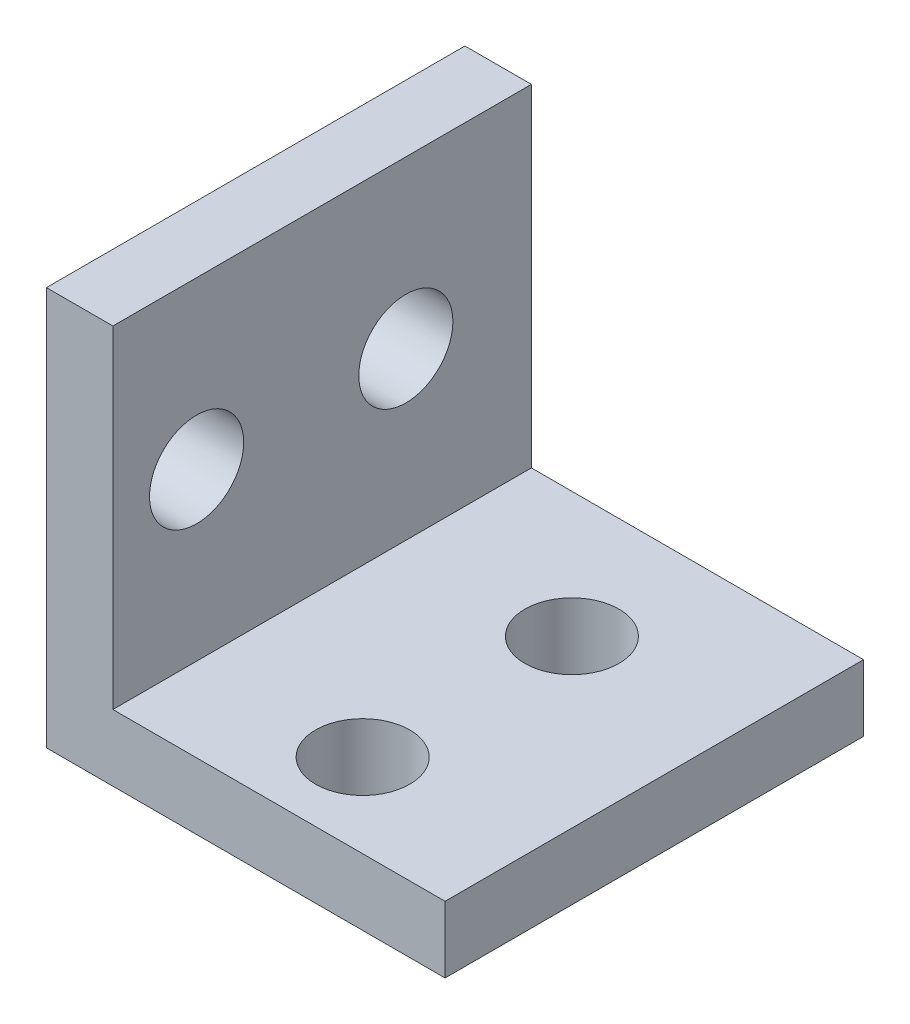
SolidWorks part; units mm, degrees
material "Aleación 6061"
ref_plane "Alzado" through (0, 0, 0) normal (0, 0, 1) x (1, 0, 0)
ref_plane "Planta" through (0, 0, 0) normal (0, 1, 0) x (1, 0, 0)
ref_plane "Vista lateral" through (0, 0, 0) normal (1, 0, 0) x (0, 0, -1)
sketch "Sk_Ala_1" plane through (0, 0, 0) normal (0, 0, 1) x (1, 0, 0)
  line L1 (0, 0) -> (19.05, 0)
  line L2 (0, 0) -> (0, 3.175)
  line L3 (0, 3.175) -> (19.05, 3.175)
  line L4 (19.05, 0) -> (19.05, 3.175)
  line L5 (0, 0) -> (19.05, 3.175) construction
  line L6 (0, 3.175) -> (19.05, 0) construction
  point P0 (9.525, 1.5875)
  dimension "D1" = 19.05
  dimension "D2" = 3.175
  dimension "D3" = 9.525
  dimension "D4" = 1.5875
extrude "Ala_1" add sketch "Sk_Ala_1" along normal blind 20
sketch "Sk_Ala_2" plane through (0, 0, 0) normal (0, 0, 1) x (1, 0, 0)
  line L1 (0, 0) -> (3.175, 0)
  line L2 (0, 0) -> (0, 19.05)
  line L3 (0, 19.05) -> (3.175, 19.05)
  line L4 (3.175, 0) -> (3.175, 19.05)
  line L5 (0, 0) -> (3.175, 19.05) construction
  line L6 (0, 19.05) -> (3.175, 0) construction
  point P0 (1.5875, 9.525)
  dimension "D1" = 3.175
  dimension "D2" = 19.05
  dimension "D3" = 1.5875
  dimension "D4" = 9.525
extrude "Ala_2" add sketch "Sk_Ala_2" along normal blind 20
sketch "Sk_Barrenos_ala_1" plane through (0, 0, 0) normal (0, 1, 0) x (1, 0, 0)
  circle A0 centre (11.1125, -6) radius 2.25
  circle A1 centre (11.1125, -16) radius 2.25
  dimension "D1" = 4.5
  dimension "D4" = 4.5
  dimension "D2" = 11.1125
  dimension "D3" = 6
  dimension "D5" = 11.1125
  dimension "D6" = 16
extrude "Barrenos_ala_1" cut sketch "Sk_Barrenos_ala_1" along normal blind 3.175
sketch "Sk_Barrenos_ala_2" plane through (0, 0, 0) normal (1, 0, 0) x (0, 0, -1)
  circle A0 centre (-6, 11.1125) radius 2.25
  circle A1 centre (-16, 11.1125) radius 2.25
  dimension "D1" = 4.5
  dimension "D4" = 4.5
  dimension "D2" = 6
  dimension "D3" = 11.1125
  dimension "D5" = 16
  dimension "D6" = 11.1125
extrude "Barrenos_ala_2" cut sketch "Sk_Barrenos_ala_2" along normal blind 3.175
